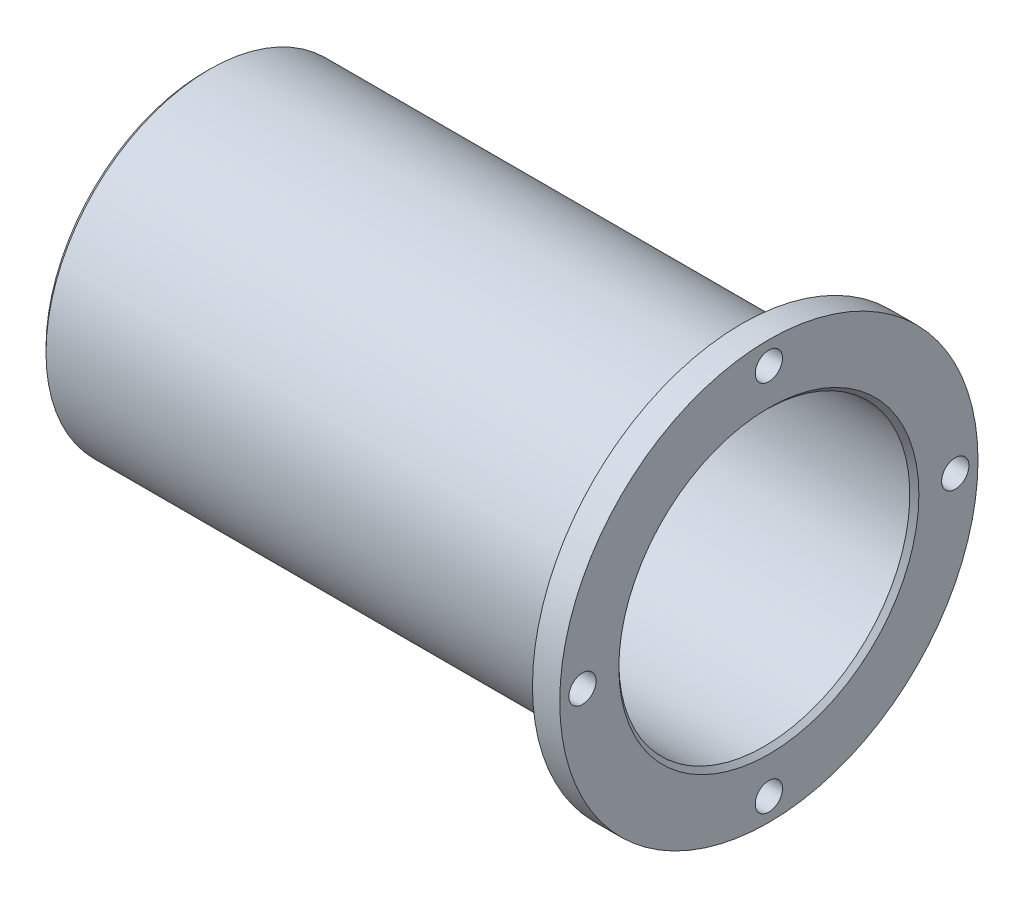
SolidWorks part; units mm, degrees
material "6061-T6 (SS)"
ref_plane "前视基准面" through (0, 0, 0) normal (0, 0, 1) x (1, 0, 0)
ref_plane "上视基准面" through (0, 0, 0) normal (0, 1, 0) x (1, 0, 0)
ref_plane "右视基准面" through (0, 0, 0) normal (1, 0, 0) x (0, 0, -1)
sketch "草图1" plane through (0, 0, 0) normal (0, 0, 1) x (1, 0, 0)
  line L0 (-69.9562, 0) -> (48.2051, 0) construction
  line L1 (0, 45.5597) -> (0, -40.3865) construction
  line L2 (-62, 18) -> (-62, 9.5)
  line L3 (-60, 16) -> (0, 16)
  line L4 (-62, 18) -> (-3, 18)
  line L5 (-3, 18) -> (-3, 23)
  line L6 (-3, 23) -> (0, 23)
  line L7 (0, 23) -> (0, 16)
  line L8 (-60, 16) -> (-60, 9.5)
  line L9 (-60, 9.5) -> (-62, 9.5)
  dimension "D1" = 46
  dimension "D2" = 36
  dimension "D3" = 32
  dimension "D4" = 3
  dimension "D5" = 2
  dimension "D6" = 57
  dimension "D7" = 19
revolve "旋转1" add sketch "草图1" angle 360 about L0
sketch "草图2" plane through (-62, 0, 0) normal (-1, 0, 0) x (0, 0, 1)
  circle A0 centre (0, 0) radius 13 construction
  circle A1 centre (0, 13) radius 1.5
  circle A2 centre (13, 0) radius 1.5
  circle A3 centre (0, -13) radius 1.5
  circle A4 centre (-13, 0) radius 1.5
  point P14 (0, 0)
  dimension "D1" = 26
  dimension "D2" = 3
  dimension "D3" = 4
extrude "切除-拉伸1" cut sketch "草图2" against normal up to next
chamfer "倒角1" distance 1.5 angle 45 4 edges at (-62, -13, 1.5) (-62, 0, 14.5) (-62, 13, 1.5) (-62, 0, -11.5)
sketch "草图3" plane through (0, 0, 0) normal (1, 0, 0) x (0, 0, -1)
  circle A0 centre (0, 0) radius 20.5 construction
  circle A1 centre (0, 20.5) radius 1.5
  circle A2 centre (20.5, 0) radius 1.5
  circle A3 centre (0, -20.5) radius 1.5
  circle A4 centre (-20.5, 0) radius 1.5
  point P14 (0, 0)
  dimension "D1" = 41
  dimension "D2" = 3
  dimension "D3" = 4
extrude "切除-拉伸2" cut sketch "草图3" against normal up to next
chamfer "倒角2" distance 0.5 angle 45 2 edges at (-62, 0, 18) (0, 0, 16)
move or copy body "实体-移动/复制1" [suppressed] bodies to move or copy 108
